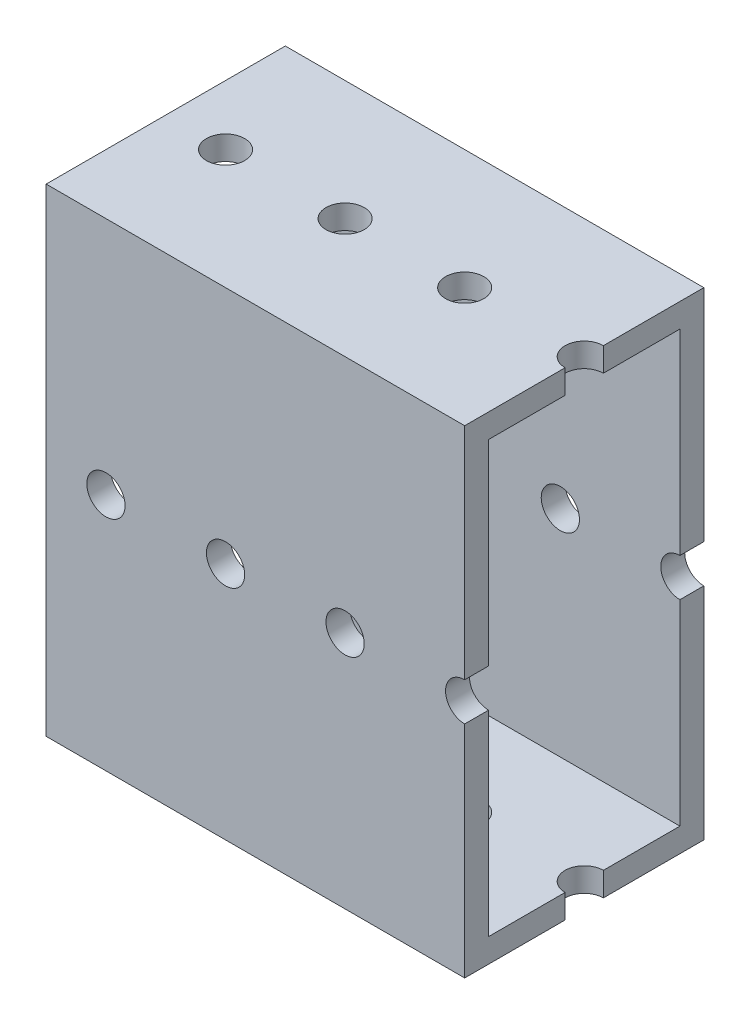
SolidWorks part; units mm, degrees
ref_plane "Front Plane" through (0, 0, 0) normal (0, 0, 1) x (1, 0, 0)
ref_plane "Top Plane" through (0, 0, 0) normal (0, 1, 0) x (1, 0, 0)
ref_plane "Right Plane" through (0, 0, 0) normal (1, 0, 0) x (0, 0, -1)
sketch "Sketch1" plane through (0, 0, 0) normal (1, 0, 0) x (0, 0, -1)
  line L0 (-10.16, 22.86) -> (10.16, 22.86)
  line L1 (-12.7, -25.4) -> (12.7, -25.4)
  line L2 (-12.7, -25.4) -> (-12.7, 25.4)
  line L3 (-12.7, 25.4) -> (12.7, 25.4)
  line L4 (12.7, -25.4) -> (12.7, 25.4)
  line L5 (-12.7, -25.4) -> (12.7, 25.4) construction
  line L6 (-12.7, 25.4) -> (12.7, -25.4) construction
  line L7 (10.16, -22.86) -> (10.16, 22.86)
  line L8 (-10.16, -22.86) -> (10.16, -22.86)
  line L9 (-10.16, -22.86) -> (-10.16, 22.86)
  point P0 (0, 0)
  dimension "D1" = 25.4
  dimension "D2" = 50.8
  dimension "D3" = 2.54
extrude "Boss-Extrude1" add sketch "Sketch1" along normal blind 44.45
sketch "Sketch4" plane through (0, -25.4, 0) normal (0, -1, 0) x (1, 0, 0)
  line L0 (0, 12.7) -> (0, -12.7) construction
  circle A0 centre (6.35, 0) radius 2.032
  circle A1 centre (19.05, 0) radius 2.032
  circle A2 centre (31.75, 0) radius 2.032
  circle A3 centre (44.45, 0) radius 2.032
  circle A4 centre (57.15, 0) radius 2.032
  circle A5 centre (69.85, 0) radius 2.032
  dimension "D2" = 4.064
  dimension "D1" = 6.35
  dimension "D3" = 6
extrude "Cut-Extrude3" cut sketch "Sketch4" against normal through all
sketch "Sketch6" plane through (0, 0, -12.7) normal (0, 0, -1) x (-1, 0, 0)
  line L0 (-44.45, -25.4) -> (-44.45, 25.4) construction
  circle A0 centre (-44.45, 0) radius 2.032
  circle A1 centre (-31.75, 0) radius 2.032
  circle A2 centre (-19.05, 0) radius 2.032
  circle A3 centre (-6.35, 0) radius 2.032
  circle A4 centre (6.35, 0) radius 2.032
  circle A5 centre (19.05, 0) radius 2.032
  circle A6 centre (31.75, 0) radius 2.032
  dimension "D1" = 4.064
  dimension "D2" = 7
extrude "Cut-Extrude5" cut sketch "Sketch6" against normal through all
